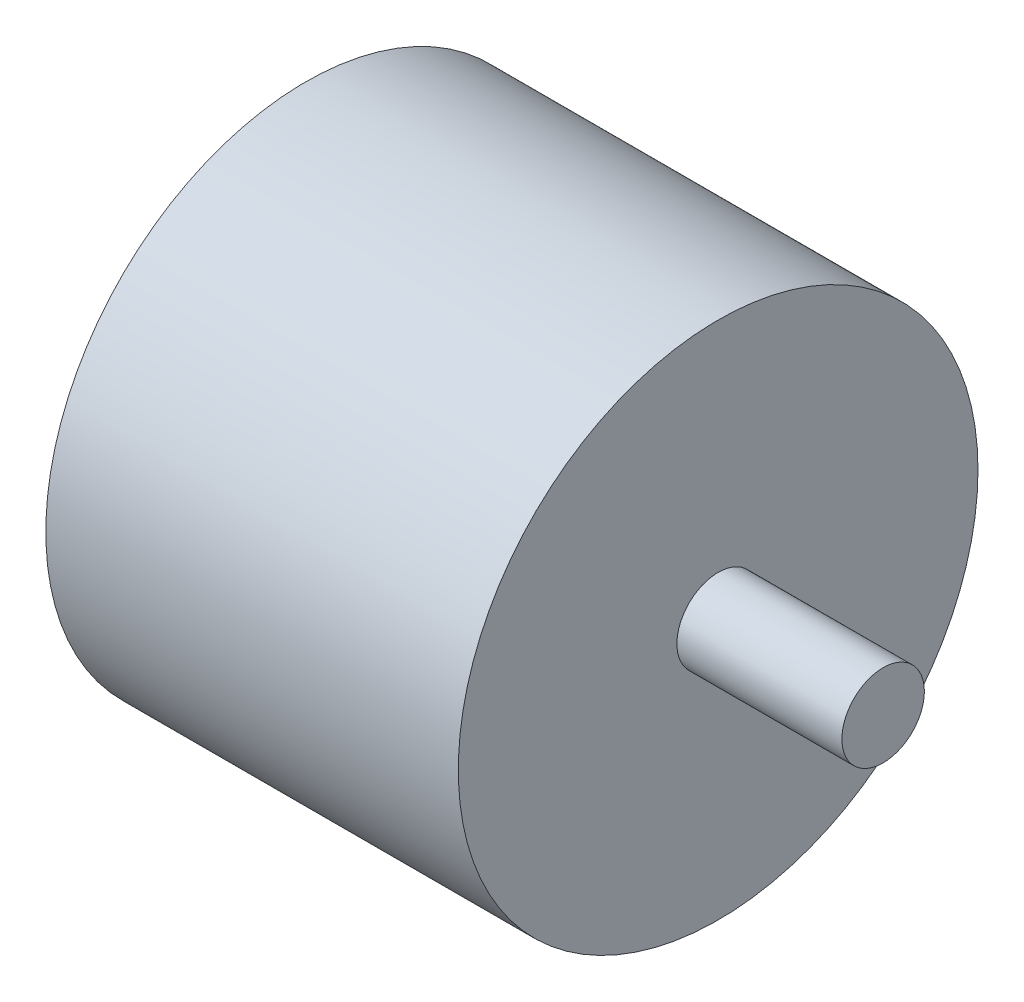
SolidWorks part; units mm, degrees
ref_plane "Front Plane" through (0, 0, 0) normal (0, 0, 1) x (1, 0, 0)
ref_plane "Top Plane" through (0, 0, 0) normal (0, 1, 0) x (1, 0, 0)
ref_plane "Right Plane" through (0, 0, 0) normal (1, 0, 0) x (0, 0, -1)
sketch "Sketch1" plane through (0, 0, 0) normal (1, 0, 0) x (0, 0, -1)
  circle A0 centre (0, 0) radius 31.5
  dimension "D1" = 63
extrude "Boss-Extrude1" add sketch "Sketch1" along normal mid plane 50
sketch "Sketch2" plane through (25, 0, 0) normal (1, 0, 0) x (0, 0, -1)
  circle A0 centre (0, 0) radius 5
  dimension "D1" = 10
shell "Shell1" thickness 5
extrude "Boss-Extrude3" add sketch "Sketch2" along normal blind 20
